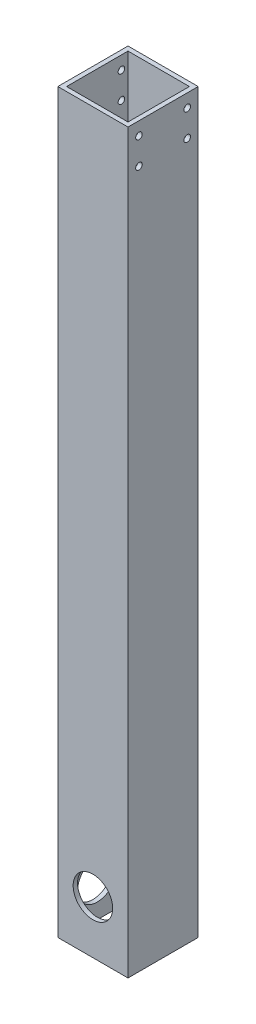
SolidWorks part; units mm, degrees
material "6063-T1"
ref_plane "Front Plane" through (0, 0, 0) normal (0, 0, 1) x (1, 0, 0)
ref_plane "Top Plane" through (0, 0, 0) normal (0, 1, 0) x (1, 0, 0)
ref_plane "Right Plane" through (0, 0, 0) normal (1, 0, 0) x (0, 0, -1)
sketch "Sketch1" plane through (0, 0, 0) normal (0, 1, 0) x (1, 0, 0)
  line L1 (-25.4, 25.4) -> (25.4, 25.4)
  line L2 (-25.4, 25.4) -> (-25.4, -25.4)
  line L3 (-25.4, -25.4) -> (25.4, -25.4)
  line L4 (25.4, 25.4) -> (25.4, -25.4)
  line L5 (-25.4, 25.4) -> (25.4, -25.4) construction
  line L6 (-25.4, -25.4) -> (25.4, 25.4) construction
  line L7 (-22.225, -22.225) -> (22.225, -22.225)
  line L8 (-22.225, -22.225) -> (-22.225, 22.225)
  line L9 (-22.225, 22.225) -> (22.225, 22.225)
  line L10 (22.225, -22.225) -> (22.225, 22.225)
  line L11 (-22.225, -22.225) -> (22.225, 22.225) construction
  line L12 (-22.225, 22.225) -> (22.225, -22.225) construction
  point P0 (0, 0)
  point P6 (0, 0)
  dimension "D1" = 50.8
  dimension "D2" = 50.8
  dimension "D3" = 3.175
  dimension "D4" = 3.175
extrude "Boss-Extrude1" add sketch "Sketch1" along normal blind 533.4
sketch "Sketch2" plane through (-25.4, 0, 0) normal (-1, 0, 0) x (0, 0, 1)
  line L0 (-25.4, 0) -> (25.4, 0) construction
  circle A0 centre (0, 25.4) radius 14.2875
  dimension "D1" = 28.575
  dimension "D2" = 25.4
extrude "Cut-Extrude1" cut sketch "Sketch2" against normal blind 3.175
sketch "Sketch3" plane through (0, 0, -25.4) normal (0, 0, -1) x (-1, 0, 0)
  line L0 (-25.4, 0) -> (25.4, 0) construction
  circle A0 centre (0, 38.1) radius 14.3002
  dimension "D1" = 28.6004
  dimension "D2" = 38.1
extrude "Cut-Extrude2" cut sketch "Sketch3" against normal through all
sketch "Sketch4" plane through (-25.4, 0, 0) normal (-1, 0, 0) x (0, 0, 1)
  line L0 (25.4, 533.4) -> (25.4, 0) construction
  line L1 (-25.4, 533.4) -> (25.4, 533.4) construction
  line L2 (0, 533.4) -> (0, 0) construction
  line L3 (-25.4, 0) -> (25.4, 0) construction
  circle A0 centre (17.4625, 523.875) radius 2.3813
  circle A1 centre (17.4625, 504.825) radius 2.3813
  circle A2 centre (-17.4625, 504.825) radius 2.3813
  circle A3 centre (-17.4625, 523.875) radius 2.3813
  point P12 (0, 0)
  dimension "D1" = 4.7625
  dimension "D2" = 7.9375
  dimension "D4" = 4.7625
  dimension "D3" = 9.525
  dimension "D5" = 19.05
extrude "Cut-Extrude3" cut sketch "Sketch4" against normal through all
